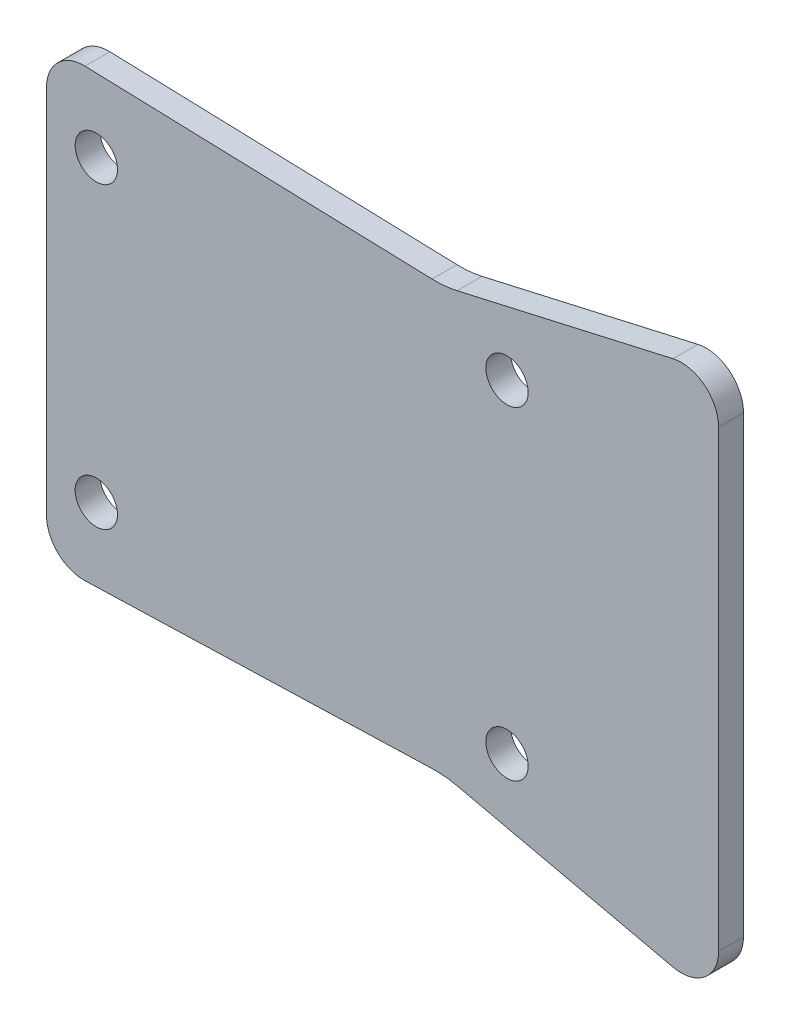
SolidWorks part; units mm, degrees
ref_plane "前视基准面" through (0, 0, 0) normal (0, 0, 1) x (1, 0, 0)
ref_plane "上视基准面" through (0, 0, 0) normal (0, 1, 0) x (1, 0, 0)
ref_plane "右视基准面" through (0, 0, 0) normal (1, 0, 0) x (0, 0, -1)
other "Configuration Table"
sketch "草图1" plane through (0, 0, 0) normal (0, 0, 1) x (1, 0, 0)
  line L0 (41.0937, -17.9033) -> (68.9761, -17.032)
  line L1 (70.9989, -17.227) -> (88.3351, -21.1671)
  line L2 (92, -18.2417) -> (92, 18.2417)
  line L3 (88.3351, 21.1671) -> (70.9989, 17.227)
  line L4 (68.9761, 17.032) -> (41.0937, 17.9033)
  line L5 (38, 14.9048) -> (38, -14.9048)
  arc A0 (38, -14.9048) -> (41.0937, -17.9033) centre (41, -14.9048) ccw
  arc A1 (68.9761, -17.032) -> (70.9989, -17.227) centre (69.226, -25.0281) cw
  arc A2 (88.3351, -21.1671) -> (92, -18.2417) centre (89, -18.2417) ccw
  arc A3 (92, 18.2417) -> (88.3351, 21.1671) centre (89, 18.2417) ccw
  arc A4 (70.9989, 17.227) -> (68.9761, 17.032) centre (69.226, 25.0281) cw
  arc A5 (41.0937, 17.9033) -> (38, 14.9048) centre (41, 14.9048) ccw
extrude "Underside_cover_T2" add sketch "草图1" along normal blind 2
ref_plane "Plane_z_2_1" through (0, 0, 2) normal (0, 0, 1) x (1, 0, 0)
sketch "草图2" plane through (0, 0, 2) normal (0, 0, 1) x (1, 0, 0)
  circle A0 centre (42, -12) radius 1.7
  circle A1 centre (42, 12) radius 1.7
  circle A2 centre (75, -13) radius 1.7
  circle A3 centre (75, 13) radius 1.7
extrude "Closure_only_four_M3_holes" cut sketch "草图2" against normal blind 2
